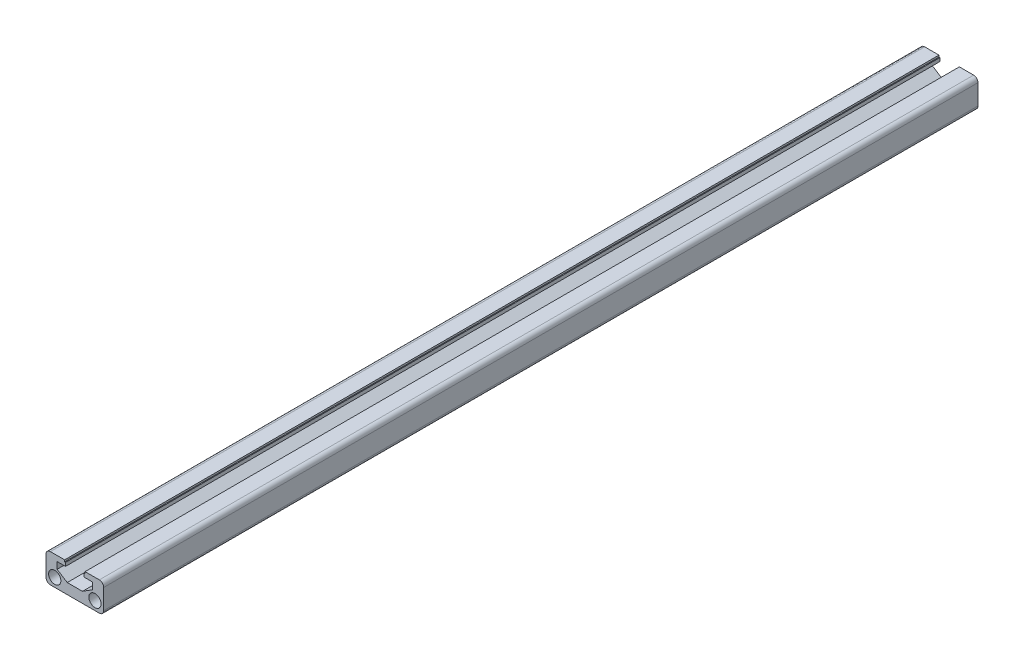
SolidWorks part; units mm, degrees
ref_plane "前视基准面" through (0, 0, 0) normal (0, 0, 1) x (1, 0, 0)
ref_plane "上视基准面" through (0, 0, 0) normal (0, 1, 0) x (1, 0, 0)
ref_plane "右视基准面" through (0, 0, 0) normal (1, 0, 0) x (0, 0, -1)
other "Configuration Table"
sketch "草图1" plane through (0, 0, 0) normal (0, 0, 1) x (1, 0, 0)
  line L0 (8.4, -4.95) -> (-8.4, -4.95)
  line L1 (-9.9, -3.45) -> (-9.9, 3.45)
  line L2 (-8.4, 4.95) -> (-3.5, 4.95)
  line L3 (-3.5, 4.95) -> (-3.5, 4.3385)
  line L4 (-3.5, 4.3385) -> (-3.2, 4.3385)
  line L5 (-3.2, 4.3385) -> (-3.2, 3.15)
  line L6 (-3.2, 3.15) -> (-6.0748, 3.15)
  line L7 (-6.0748, 3.15) -> (-6.0748, 0.843)
  line L8 (-6.0748, 0.843) -> (-2.6166, -1.35)
  line L9 (-2.6166, -1.35) -> (2.6166, -1.35)
  line L10 (6.0748, 0.843) -> (2.6166, -1.35)
  line L11 (6.0748, 3.15) -> (6.0748, 0.843)
  line L12 (3.2, 3.15) -> (6.0748, 3.15)
  line L13 (3.2, 4.3385) -> (3.2, 3.15)
  line L14 (3.5, 4.3385) -> (3.2, 4.3385)
  line L15 (3.5, 4.95) -> (3.5, 4.3385)
  line L16 (8.4, 4.95) -> (3.5, 4.95)
  line L17 (9.9, -3.45) -> (9.9, 3.45)
  circle A0 centre (-6.9, -1.95) radius 2.1
  arc A1 (9.9, -3.45) -> (8.4, -4.95) centre (8.4, -3.45) cw
  arc A2 (8.4, 4.95) -> (9.9, 3.45) centre (8.4, 3.45) cw
  arc A3 (-8.4, -4.95) -> (-9.9, -3.45) centre (-8.4, -3.45) cw
  arc A4 (-9.9, 3.45) -> (-8.4, 4.95) centre (-8.4, 3.45) cw
  circle A5 centre (6.9, -1.95) radius 2.1
  point P12 (0, -1.35)
  point P20 (0, -4.95)
  dimension "D6" = 4.2
  dimension "D9" = 1.5
  dimension "D1" = 19.8
  dimension "D2" = 7
  dimension "D3" = 6.4
  dimension "D4" = 6.3
  dimension "D5" = 1.8
  dimension "D7" = 3
  dimension "D8" = 3
extrude "凸台-拉伸1" add sketch "草图1" along normal blind 300
